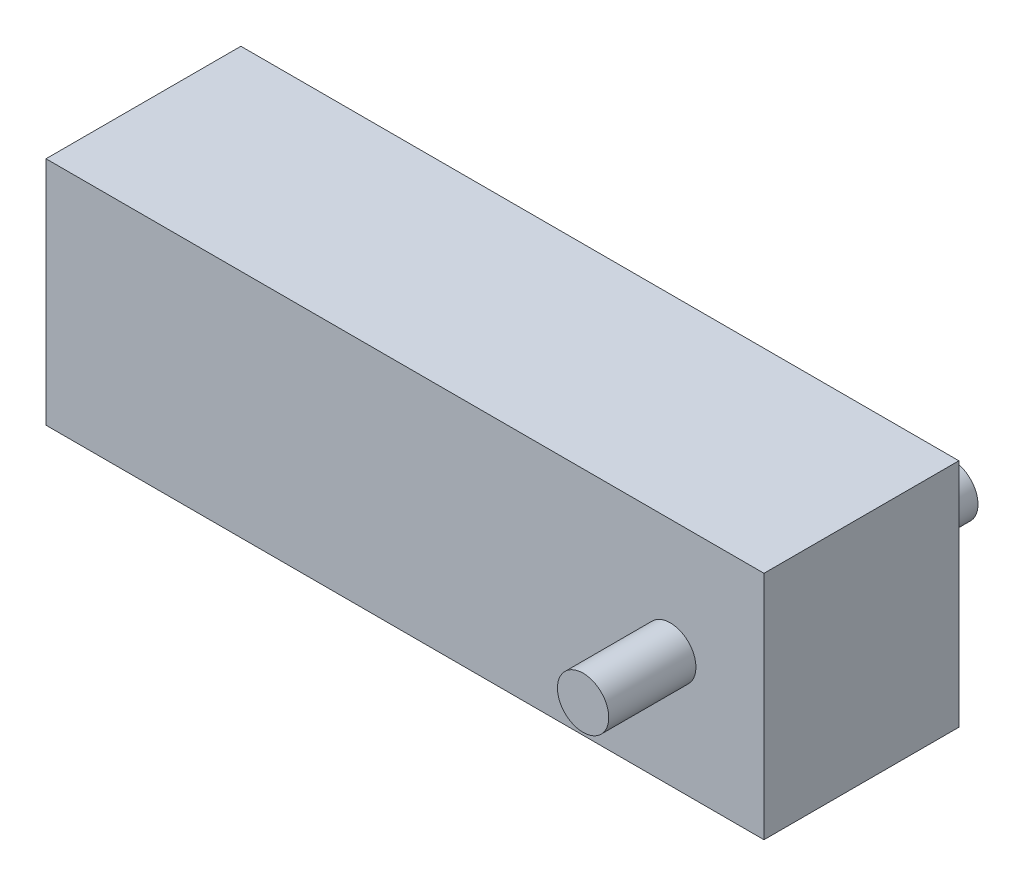
SolidWorks part; units mm, degrees
ref_plane "前视基准面" through (0, 0, 0) normal (0, 0, 1) x (1, 0, 0)
ref_plane "上视基准面" through (0, 0, 0) normal (0, 1, 0) x (1, 0, 0)
ref_plane "右视基准面" through (0, 0, 0) normal (1, 0, 0) x (0, 0, -1)
sketch "草图1" plane through (0, 0, 0) normal (0, 0, 1) x (1, 0, 0)
  line L1 (35, 11.25) -> (-35, 11.25)
  line L2 (35, 11.25) -> (35, -11.25)
  line L3 (35, -11.25) -> (-35, -11.25)
  line L4 (-35, 11.25) -> (-35, -11.25)
  line L5 (0, -11.25) -> (0, 11.25) construction
  line L6 (35, 0) -> (-35, 0) construction
  point P0 (0, 0)
  dimension "D1" = 22.5
  dimension "D2" = 70
extrude "凸台-拉伸1" add sketch "草图1" along normal mid plane 19
sketch "草图2" plane through (0, 0, 9.5) normal (0, 0, 1) x (1, 0, 0)
  line L0 (0, 0) -> (29.8444, 0) construction
  circle A0 centre (25.8652, 0) radius 2.5
  dimension "D1" = 5
extrude "凸台-拉伸2" add sketch "草图2" along normal blind 8.5
mirror "镜向1" about plane through (0, 0, 0) normal (0, 0, 1) of "凸台-拉伸2"
